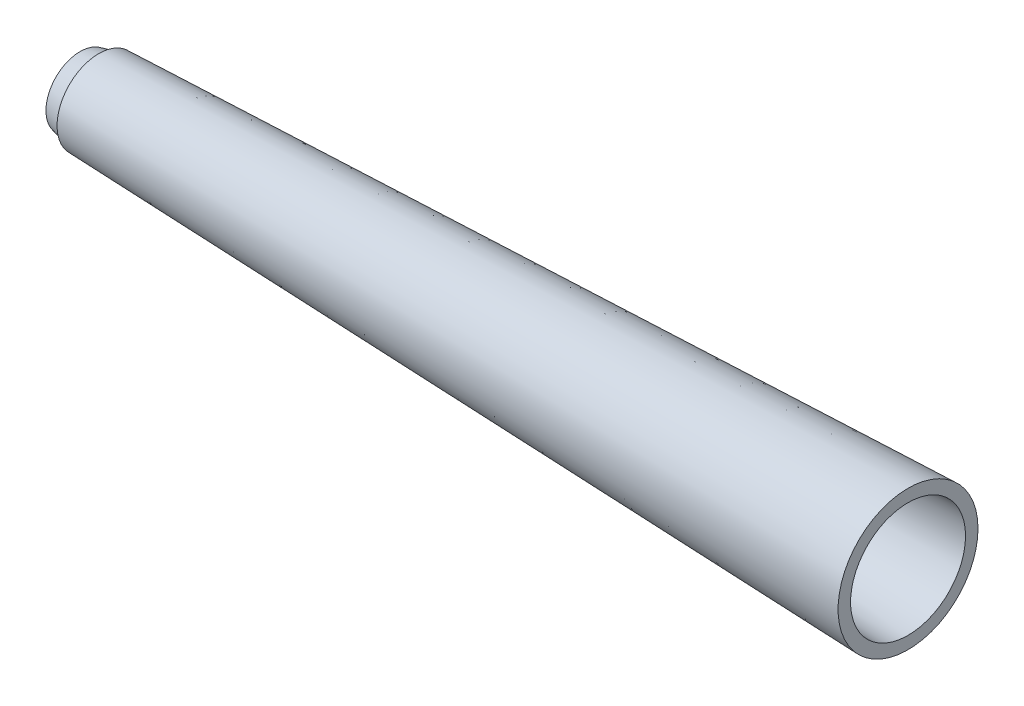
SolidWorks part; units mm, degrees
ref_plane "Front Plane" through (0, 0, 0) normal (0, 0, 1) x (1, 0, 0)
ref_plane "Top Plane" through (0, 0, 0) normal (0, 1, 0) x (1, 0, 0)
ref_plane "Right Plane" through (0, 0, 0) normal (1, 0, 0) x (0, 0, -1)
sketch "Sketch2" plane through (0, 0, 0) normal (0, 0, 1) x (1, 0, 0)
  line L0 (-19.2758, 0) -> (50, 0) construction
  line L1 (0, 21.4747) -> (0, -15.9358) construction
  line L2 (0, 1.2) -> (54.9325, 5.0413) construction
  line L3 (0, 3.2) -> (55.9028, 7.1091) construction
  line L4 (0, 1.2) -> (50, 4.6963)
  line L5 (1.8511, 3.3294) -> (50, 6.6963)
  line L6 (50, 0) -> (50, 20.2328) construction
  line L7 (50, 6.6963) -> (50, 4.6963)
  arc A0 (0, 1.2) -> (1.8511, 3.3294) centre (1.9903, 1.3392) cw
  dimension "D1" = 4
  dimension "D2" = 1.2
  dimension "D3" = 2
  dimension "D4" = 50
revolve "Revolve2" add sketch "Sketch2" angle 360 about L0
ref_plane "Plane1" through (50, 0, 0) normal (1, 0, 0) x (0, 0, -1)
ref_axis "Axis1" through (50, 0, 0) along (-1, 0, 0)
sketch "Sketch3" plane through (0, 0, 0) normal (0, 0, 1) x (1, 0, 0)
  line L0 (50, 6.6963) -> (180, 6.6963) construction
  line L1 (50, -7.366) -> (50, 7.366) construction
  line L2 (50, 6.6963) -> (1.8511, 3.3294) construction
  line L3 (50, 6.6963) -> (180, 11.236) construction
  line L4 (50, 4.6951) -> (180, 9.2348)
  line L5 (180, 9.2348) -> (180, 11.236)
  line L6 (180, 11.236) -> (50, 6.6963)
  line L7 (50, 6.6963) -> (50, 4.6951)
  dimension "D1" = 2
  dimension "D2" = 130
  dimension "D3" = 2
revolve "Revolve3" add sketch "Sketch3" angle 360 about axis through (50, 0, 0) along (-1, 0, 0)
sketch "Sketch4" plane through (0, 0, 0) normal (0, 0, 1) x (1, 0, 0)
  line L0 (50, 6.6963) -> (47.323, 6.6963) construction
  line L3 (50, 5.1963) -> (42.8414, 5.1963) construction
  line L4 (50, 6.1951) -> (47, 5.4841)
  line L5 (47, 5.4841) -> (50, 5.1963)
  line L6 (50, 6.1951) -> (50, 5.1963)
  line L7 (50, 6.6963) -> (1.8511, 3.3294) construction
  line L8 (50, -7.366) -> (50, 7.366) construction
  dimension "D1" = 1.5
  dimension "D2" = 3
  dimension "D3" = 1
  dimension "D4" = 0.5
other "SurfaceCut3"
revolve "Revolve4" add sketch "Sketch4" angle 360 about axis through (50, 0, 0) along (-1, 0, 0)
